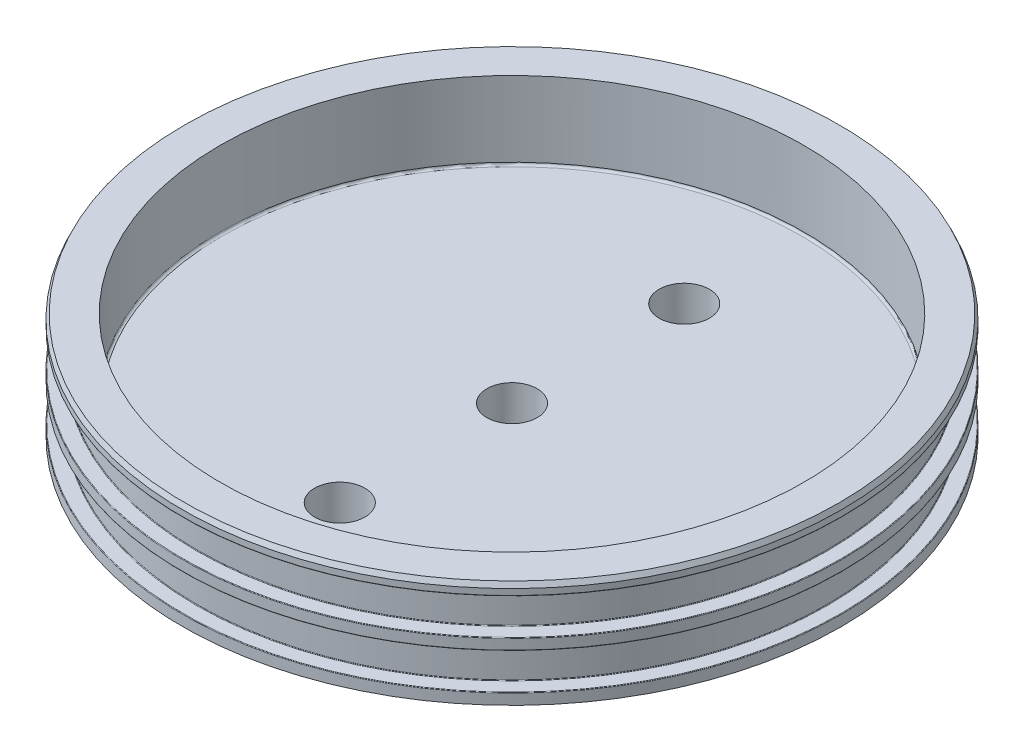
SolidWorks part; units mm, degrees
material "6061-T6 (SS)"
ref_plane "Front Plane" through (0, 0, 0) normal (0, 0, 1) x (1, 0, 0)
ref_plane "Top Plane" through (0, 0, 0) normal (0, 1, 0) x (1, 0, 0)
ref_plane "Right Plane" through (0, 0, 0) normal (1, 0, 0) x (0, 0, -1)
sketch "Sketch1" plane through (0, 0, 0) normal (0, 0, 1) x (1, 0, 0)
  line L0 (0, 48.1922) -> (0, -25.6743) construction
  line L1 (0, 0) -> (72.898, 0)
  line L2 (72.898, 0) -> (72.898, 2.4638)
  line L3 (72.898, 2.4638) -> (69.6468, 2.4638)
  line L4 (69.6468, 2.4638) -> (69.6468, 10.4648)
  line L5 (69.6468, 10.4648) -> (72.898, 10.4648)
  line L6 (72.898, 10.4648) -> (72.898, 12.9286)
  line L7 (72.898, 12.9286) -> (69.6468, 12.9286)
  line L8 (64.5668, 23.4696) -> (64.5668, 6.35)
  line L9 (64.5668, 6.35) -> (0, 6.35)
  line L10 (0, 6.35) -> (0, 0)
  line L11 (69.6468, 12.9286) -> (69.6468, 20.9296)
  line L12 (69.6468, 20.9296) -> (72.898, 20.9296)
  line L13 (72.898, 20.9296) -> (72.898, 23.4696)
  line L14 (72.898, 23.4696) -> (64.5668, 23.4696)
  dimension "D1" = 145.796
  dimension "D2" = 8.001
  dimension "D5" = 6.35
  dimension "D7" = 8.001
  dimension "D4" = 2.4638
  dimension "D8" = 2.54
  dimension "D3" = 69.6468
  dimension "D6" = 5.08
revolve "Revolve1" add sketch "Sketch1" angle 360 about L0
sketch "Sketch6" plane through (0, 0, 0) normal (0, -1, 0) x (1, 0, 0)
  circle A0 centre (0, 0) radius 66.04
  dimension "D1" = 132.08
extrude "Boss-Extrude1" add sketch "Sketch6" along normal blind 2.54
hole_wizard "Pipe Tap Drill for 1/4 Tap - GN2" positions "Sketch2" profile "Sketch3" hole size "1/4" standard "ANSI Inch" end condition through all
sketch "Sketch2" plane through (0, 6.35, 0) normal (0, 1, 0) x (1, 0, 0)
  point P4 (0, 0)
  dimension "D1" = 0
sketch "Sketch3" plane through (0, 6.35, 0) normal (1, 0, 0) x (0, 0, 1)
  line L0 (0, 0) -> (0, 8.89)
  line L1 (0, 8.89) -> (5.5626, 8.89)
  line L2 (5.5626, 8.89) -> (5.5626, 0)
  line L5 (5.5626, 0) -> (0, 0)
  line L11 (0, -6.35) -> (0, 107.95) construction
  dimension "Thru Hole Dia." = 11.1252
  dimension "Thru Hole Depth" = 8.89
fillet "CNC ID Fillet" radius 0.127 5 edges at (-69.6468, 10.4648, 0) (-69.6468, 2.4638, 0) (-69.6468, 20.9296, 0) (-69.6468, 12.9286, 0) (66.04, 0, 0)
fillet "CNC OD Fillet" radius 0.127 5 edges at (-72.898, 10.4648, 0) (-72.898, 2.4638, 0) (66.04, -2.54, 0) (-72.898, 20.9296, 0) (-72.898, 12.9286, 0)
chamfer "CNC Chamfers" distance 0.508 angle 65 1 edges at (-72.898, 23.4696, 0)
fillet "CNC Bore Fillet" radius 0.508 1 edges at (-64.5668, 6.35, 0)
hole_wizard "Pipe Tap Drill for 1/4 Tap - Relief Valve" positions "Sketch13" profile "Sketch14" hole size "1/4" standard "ANSI Inch" end condition through all
sketch "Sketch13" plane through (0, -2.54, 0) normal (0, -1, 0) x (-1, 0, 0)
  point P4 (0, 38.1)
  dimension "D1" = 38.1
sketch "Sketch14" plane through (0, -2.54, -38.1) normal (1, 0, 0) x (0, 0, -1)
  line L0 (0, 0) -> (0, 26.0096)
  line L1 (0, 26.0096) -> (5.5626, 26.0096)
  line L2 (5.5626, 26.0096) -> (5.5626, 0)
  line L5 (5.5626, 0) -> (0, 0)
  line L11 (0, -6.35) -> (0, 107.95) construction
  dimension "Thru Hole Dia." = 11.1252
  dimension "Thru Hole Depth" = 26.0096
hole_wizard "Pipe Tap Drill for 1/4 Tap - Vent Valve" positions "Sketch15" profile "Sketch16" hole size "1/4" standard "ANSI Inch" end condition through all
sketch "Sketch15" plane through (0, -2.54, 0) normal (0, -1, 0) x (-1, 0, 0)
  point P4 (0, -38.1)
  dimension "D1" = 38.1
sketch "Sketch16" plane through (0, -2.54, 38.1) normal (1, 0, 0) x (0, 0, -1)
  line L0 (0, 0) -> (0, 26.0096)
  line L1 (0, 26.0096) -> (5.5626, 26.0096)
  line L2 (5.5626, 26.0096) -> (5.5626, 0)
  line L5 (5.5626, 0) -> (0, 0)
  line L11 (0, -6.35) -> (0, 107.95) construction
  dimension "Thru Hole Dia." = 11.1252
  dimension "Thru Hole Depth" = 26.0096
equation "\"D3@Sketch1\"=5.484/2"
